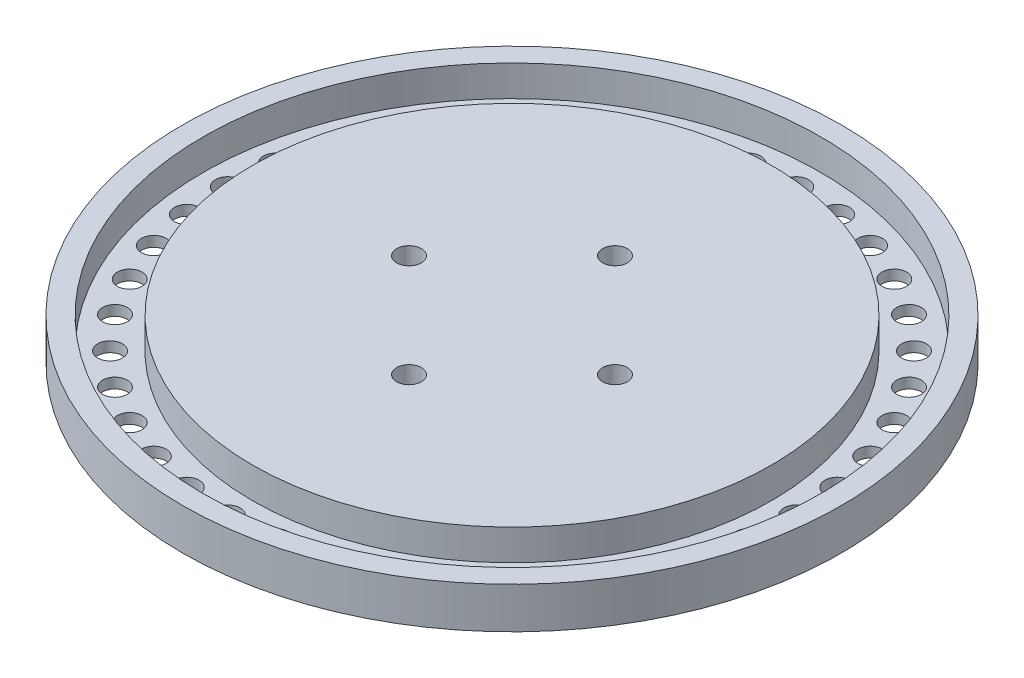
SolidWorks part; units mm, degrees
ref_plane "Front Plane" through (0, 0, 0) normal (0, 0, 1) x (1, 0, 0)
ref_plane "Top Plane" through (0, 0, 0) normal (0, 1, 0) x (1, 0, 0)
ref_plane "Right Plane" through (0, 0, 0) normal (1, 0, 0) x (0, 0, -1)
sketch "Sketch1" plane through (0, 0, 0) normal (0, 1, 0) x (1, 0, 0)
  line L0 (0, 0) -> (0, -34.5) construction
  circle A0 centre (0, 0) radius 29.5 construction
  circle A1 centre (0, 0) radius 40
  circle A2 centre (0, 0) radius 32 construction
  circle A6 centre (0, 0) radius 37 construction
  circle A7 centre (0, 0) radius 34.5 construction
  circle A8 centre (0, -34.5) radius 1.5
  circle A9 centre (-5.397, -34.0752) radius 1.5
  circle A10 centre (-10.6611, -32.8114) radius 1.5
  circle A11 centre (-15.6627, -30.7397) radius 1.5
  circle A12 centre (-20.2786, -27.9111) radius 1.5
  circle A13 centre (-24.3952, -24.3952) radius 1.5
  circle A14 centre (-27.9111, -20.2786) radius 1.5
  circle A15 centre (-30.7397, -15.6627) radius 1.5
  circle A16 centre (-32.8114, -10.6611) radius 1.5
  circle A17 centre (-34.0752, -5.397) radius 1.5
  circle A18 centre (-34.5, 0) radius 1.5
  circle A19 centre (-34.0752, 5.397) radius 1.5
  circle A20 centre (-32.8114, 10.6611) radius 1.5
  circle A21 centre (-30.7397, 15.6627) radius 1.5
  circle A22 centre (-27.9111, 20.2786) radius 1.5
  circle A23 centre (-24.3952, 24.3952) radius 1.5
  circle A24 centre (-20.2786, 27.9111) radius 1.5
  circle A25 centre (-15.6627, 30.7397) radius 1.5
  circle A26 centre (-10.6611, 32.8114) radius 1.5
  circle A27 centre (-5.397, 34.0752) radius 1.5
  circle A28 centre (0, 34.5) radius 1.5
  circle A29 centre (5.397, 34.0752) radius 1.5
  circle A30 centre (10.6611, 32.8114) radius 1.5
  circle A31 centre (15.6627, 30.7397) radius 1.5
  circle A32 centre (20.2786, 27.9111) radius 1.5
  circle A33 centre (24.3952, 24.3952) radius 1.5
  circle A34 centre (27.9111, 20.2786) radius 1.5
  circle A35 centre (30.7397, 15.6627) radius 1.5
  circle A36 centre (32.8114, 10.6611) radius 1.5
  circle A37 centre (34.0752, 5.397) radius 1.5
  circle A38 centre (34.5, 0) radius 1.5
  circle A39 centre (34.0752, -5.397) radius 1.5
  circle A40 centre (32.8114, -10.6611) radius 1.5
  circle A41 centre (30.7397, -15.6627) radius 1.5
  circle A42 centre (27.9111, -20.2786) radius 1.5
  circle A43 centre (24.3952, -24.3952) radius 1.5
  circle A44 centre (20.2786, -27.9111) radius 1.5
  circle A45 centre (15.6627, -30.7397) radius 1.5
  circle A46 centre (10.6611, -32.8114) radius 1.5
  circle A47 centre (5.397, -34.0752) radius 1.5
  circle A48 centre (0, 0) radius 12.5 construction
  circle A49 centre (0, -12.5) radius 1.5
  circle A50 centre (-12.5, 0) radius 1.5
  circle A51 centre (0, 12.5) radius 1.5
  circle A52 centre (12.5, 0) radius 1.5
  point P91 (0, 0)
  point P102 (0, 0)
  dimension "D1" = 59
  dimension "D2" = 80
  dimension "D3" = 64
  dimension "D4" = 5
  dimension "D5" = 2.5
  dimension "D6" = 3
  dimension "D7" = 40
  dimension "D8" = 25
  dimension "D9" = 3
  dimension "D10" = 4
extrude "Boss-Extrude1" add sketch "Sketch1" along normal blind 5
sketch "Sketch2" plane through (0, 5, 0) normal (0, 1, 0) x (1, 0, 0)
  circle A0 centre (0, 0) radius 31.5
  circle A1 centre (0, 0) radius 37.5
  dimension "D1" = 63
  dimension "D2" = 6
extrude "Cut-Extrude1" cut sketch "Sketch2" against normal blind 3.75
